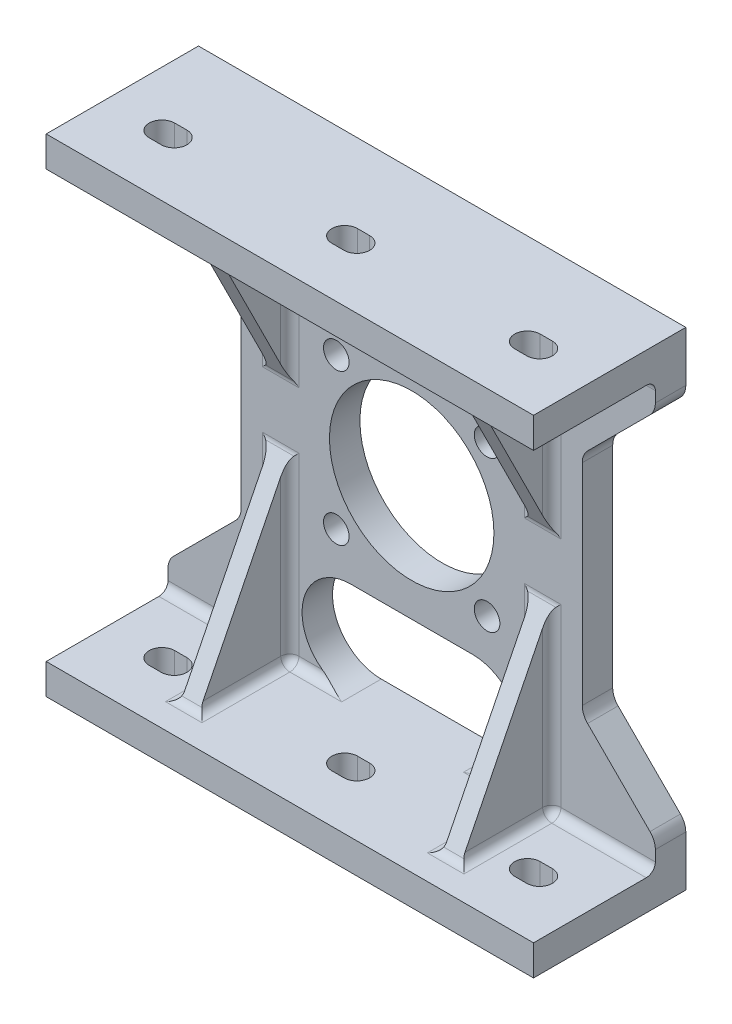
SolidWorks part; units mm, degrees
material "6061-O (SS)"
ref_plane "前视基准面" through (0, 0, 0) normal (0, 0, 1) x (1, 0, 0)
ref_plane "上视基准面" through (0, 0, 0) normal (0, 1, 0) x (1, 0, 0)
ref_plane "右视基准面" through (0, 0, 0) normal (1, 0, 0) x (0, 0, -1)
sketch "草图1" plane through (0, 0, 0) normal (0, 0, 1) x (1, 0, 0)
  line L1 (-40, 40) -> (40, 40)
  line L2 (-40, 40) -> (-40, -40)
  line L3 (-40, -40) -> (40, -40)
  line L4 (40, 40) -> (40, -40)
  line L5 (-40, 40) -> (40, -40) construction
  line L6 (-40, -40) -> (40, 40) construction
  circle A0 centre (0, 0) radius 13.5
  point P0 (0, 0)
  dimension "D3" = 27
  dimension "D1" = 80
  dimension "D2" = 80
extrude "凸台-拉伸1" add sketch "草图1" along normal blind 5
sketch "草图2" plane through (0, 0, 5) normal (0, 0, 1) x (1, 0, 0)
  line L0 (-12.3744, -12.3744) -> (-12.3744, 12.3744) construction
  line L1 (-12.3744, -12.3744) -> (12.3744, -12.3744) construction
  line L2 (-12.3744, 12.3744) -> (12.3744, 12.3744) construction
  line L3 (12.3744, -12.3744) -> (12.3744, 12.3744) construction
  line L4 (-12.3744, -12.3744) -> (12.3744, 12.3744) construction
  line L5 (-12.3744, 12.3744) -> (12.3744, -12.3744) construction
  line L7 (0, 0) -> (25.0457, 0) construction
  circle A0 centre (-12.3744, 12.3744) radius 2.1
  circle A1 centre (12.3744, 12.3744) radius 2.1
  circle A2 centre (-12.3744, -12.3744) radius 2.1
  circle A3 centre (12.3744, -12.3744) radius 2.1
  circle A4 centre (0, 0) radius 17.5 construction
  point P1 (0, 0)
  dimension "D2" = 4.2
  dimension "D3" = 4.2
  dimension "D4" = 4.2
  dimension "D5" = 4.2
  dimension "D6" = 35
  dimension "D1" = 35
  dimension "D7" = 45
extrude "切除-拉伸1" cut sketch "草图2" against normal blind 5
sketch "草图3" plane through (0, 40, 0) normal (0, 1, 0) x (1, 0, 0)
  line L0 (-40, -5) -> (-40, 0) construction
  line L1 (40, -5) -> (-40, -5)
  line L2 (40, -5) -> (40, -25)
  line L3 (40, -25) -> (-40, -25)
  line L4 (-40, -5) -> (-40, -25)
  dimension "D1" = 20
extrude "凸台-拉伸2" add sketch "草图3" against normal blind 5
sketch "草图4" plane through (0, 40, 0) normal (0, 1, 0) x (1, 0, 0)
  line L0 (0, 0) -> (0, -25) construction
  line L1 (40, 0) -> (-40, 0) construction
  line L2 (-40, -25) -> (40, -25) construction
  line L3 (-31, -15) -> (-29, -15) construction
  line L4 (-31, -12.9) -> (-29, -12.9)
  line L5 (-31, -17.1) -> (-29, -17.1)
  line L6 (-1, -15) -> (1, -15) construction
  line L7 (-1, -12.9) -> (1, -12.9)
  line L8 (-1, -17.1) -> (1, -17.1)
  line L9 (29, -15) -> (31, -15) construction
  line L10 (29, -12.9) -> (31, -12.9)
  line L11 (29, -17.1) -> (31, -17.1)
  arc A3 (-31, -12.9) -> (-31, -17.1) centre (-31, -15) ccw
  arc A4 (-29, -17.1) -> (-29, -12.9) centre (-29, -15) ccw
  arc A5 (-1, -12.9) -> (-1, -17.1) centre (-1, -15) ccw
  arc A6 (1, -17.1) -> (1, -12.9) centre (1, -15) ccw
  arc A7 (29, -12.9) -> (29, -17.1) centre (29, -15) ccw
  arc A8 (31, -17.1) -> (31, -12.9) centre (31, -15) ccw
  point P14 (-30, -15)
  point P19 (0, -15)
  point P26 (30, -15)
  dimension "D8" = 2.1
  dimension "D9" = 2.1
  dimension "D10" = 2.1
  dimension "D11" = 2
  dimension "D12" = 2
  dimension "D13" = 2
extrude "切除-拉伸2" cut sketch "草图4" against normal blind 5
fillet "圆角1" radius 1.5 1 edges at (0, 35, 5)
ref_plane "基准面1" through (0, 0, 0) normal (0, 1, 0) x (1, 0, 0)
mirror "镜向1" about plane through (0, 0, 0) normal (0, 1, 0) of "圆角1", "切除-拉伸2", "凸台-拉伸2"
ref_plane "基准面2" through (0, 0, 0) normal (1, 0, 0) x (0, 0, -1)
ref_plane "基准面3" through (-20, 0, 0) normal (-1, 0, 0) x (0, 0, 1)
sketch "草图5" plane through (-20, 0, 0) normal (-1, 0, 0) x (0, 0, 1)
  line L0 (20, 35) -> (5, 5)
  line L1 (6.5, 35) -> (25, 35) construction
  line L2 (5, 33.5) -> (5, -33.5) construction
  line L3 (5, 5) -> (5, 35)
  line L4 (5, 35) -> (20, 35)
  line L5 (20, -35) -> (5, -5)
  line L6 (6.5, -35) -> (25, -35) construction
  line L7 (5, -5) -> (5, -35)
  line L8 (5, -35) -> (20, -35)
  dimension "D1" = 15
  dimension "D2" = 30
  dimension "D3" = 15
  dimension "D4" = 30
extrude "凸台-拉伸3" add sketch "草图5" along normal blind 3
fillet "圆角2" radius 1.5 16 edges at (-20, -35, 13.25) (-20, -34.5607, 5.4393) (-20, 35, 13.25) (-20, 34.5607, 5.4393) (-23, -35, 13.25) (-23, -34.5607, 5.4393) (-23, 35, 13.25) (-23, 34.5607, 5.4393) (-21.5, -35, 20) (-20, -19.25, 5) (-20, 19.25, 5) (-23, -19.25, 5) (-21.5, -5, 5) (-21.5, 35, 20) (-21.5, 5, 5) (-23, 19.25, 5)
mirror "镜向2" about plane through (0, 0, 0) normal (1, 0, 0) of "凸台-拉伸3", "圆角2"
sketch "草图6" plane through (0, 0, 5) normal (0, 0, 1) x (1, 0, 0)
  line L0 (-40, 30.5) -> (-28.8787, 19.3787)
  line L1 (-40, 33.5) -> (-40, -33.5) construction
  line L2 (-28, 17.2574) -> (-28, -17.2574)
  line L3 (-28.8787, -19.3787) -> (-40, -30.5)
  line L4 (-40, -30.5) -> (-40, 30.5)
  line L5 (-24.5, 33.5) -> (-40, 33.5) construction
  line L6 (-40, -33.5) -> (-24.5, -33.5) construction
  line L7 (0, -13.75) -> (0, 13.75) construction
  line L8 (40, -30.5) -> (40, 30.5)
  line L9 (28.8787, -19.3787) -> (40, -30.5)
  line L10 (28, 17.2574) -> (28, -17.2574)
  line L11 (40, 30.5) -> (28.8787, 19.3787)
  arc A0 (28.8787, -19.3787) -> (28, -17.2574) centre (31, -17.2574) cw
  arc A1 (28, 17.2574) -> (28.8787, 19.3787) centre (31, 17.2574) cw
  arc A2 (-28, -17.2574) -> (-28.8787, -19.3787) centre (-31, -17.2574) cw
  arc A3 (-28.8787, 19.3787) -> (-28, 17.2574) centre (-31, 17.2574) cw
  point P18 (28, -18.5)
  point P21 (28, 18.5)
  point P24 (-28, -18.5)
  point P27 (-28, 18.5)
  dimension "D6" = 3
  dimension "D1" = 45
  dimension "D2" = 45
  dimension "D3" = 3
  dimension "D4" = 3
  dimension "D5" = 12
extrude "切除-拉伸3" cut sketch "草图6" against normal blind 10
fillet "圆角3" radius 3 4 edges at (-40, -30.5, 2.5) (-40, 30.5, 2.5) (40, 30.5, 2.5) (40, -30.5, 2.5)
sketch "草图7" plane through (0, 0, 5) normal (0, 0, 1) x (1, 0, 0)
  line L0 (-10, 27) -> (10, 27) construction
  line L1 (-10, 35) -> (10, 35)
  line L2 (-10, 19) -> (10, 19)
  line L3 (-10, -27) -> (10, -27) construction
  line L4 (-10, -19) -> (10, -19)
  line L5 (-10, -35) -> (10, -35)
  line L6 (0, -13.75) -> (0, 13.75) construction
  line L7 (18.5, 33.5) -> (-18.5, 33.5) construction
  line L8 (-18.5, -33.5) -> (18.5, -33.5) construction
  arc A0 (-10, 35) -> (-10, 19) centre (-10, 27) ccw
  arc A1 (10, 19) -> (10, 35) centre (10, 27) ccw
  arc A2 (-10, -19) -> (-10, -35) centre (-10, -27) ccw
  arc A3 (10, -35) -> (10, -19) centre (10, -27) ccw
  point P2 (0, 27)
  point P7 (0, -27)
  dimension "D1" = 8
  dimension "D2" = 8
  dimension "D3" = 20
  dimension "D4" = 20
  dimension "D5" = 6.5
  dimension "D6" = 6.5
extrude "切除-拉伸4" cut sketch "草图7" against normal blind 10 and the other way blind 10
